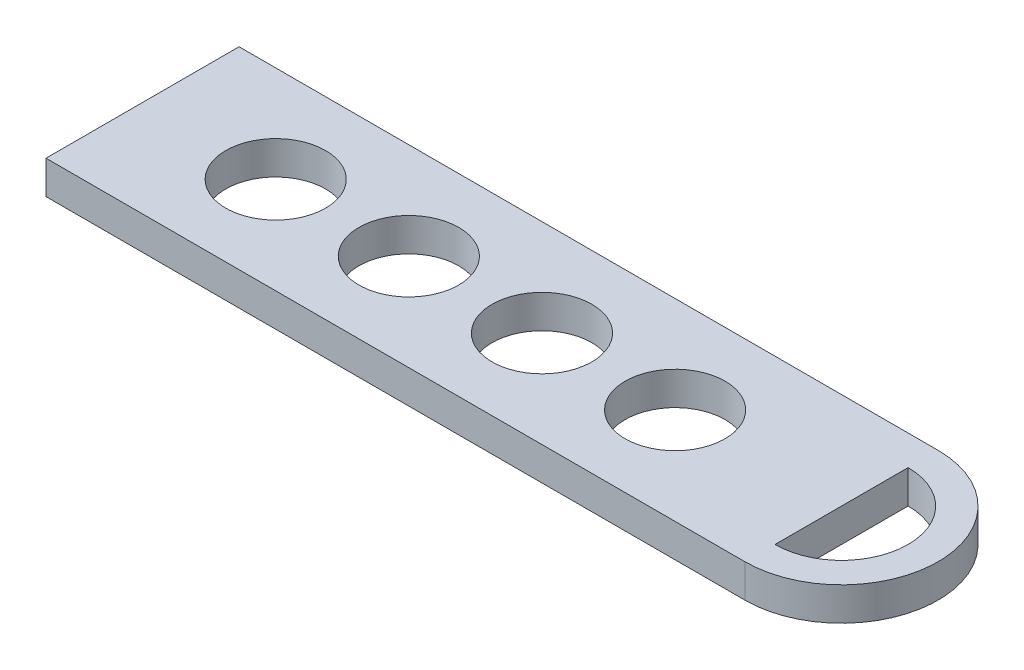
SolidWorks part; units mm, degrees
material "Perspex (TM) GS Acrylic Cast Sheet"
ref_plane "Front Plane" through (0, 0, 0) normal (0, 0, 1) x (1, 0, 0)
ref_plane "Top Plane" through (0, 0, 0) normal (0, 1, 0) x (1, 0, 0)
ref_plane "Right Plane" through (0, 0, 0) normal (1, 0, 0) x (0, 0, -1)
sketch "Sketch1" plane through (0, 0, 0) normal (1, 0, 0) x (0, 0, -1)
  line L1 (-14.5, -2.5) -> (14.5, -2.5)
  line L2 (-14.5, -2.5) -> (-14.5, 2.5)
  line L3 (-14.5, 2.5) -> (14.5, 2.5)
  line L4 (14.5, -2.5) -> (14.5, 2.5)
  line L5 (-14.5, -2.5) -> (14.5, 2.5) construction
  line L6 (-14.5, 2.5) -> (14.5, -2.5) construction
  point P0 (0, 0)
  dimension "D1" = 29
  dimension "D2" = 5
extrude "Boss-Extrude1" add sketch "Sketch1" along normal blind 105
sketch "Sketch2" plane through (0, -2.5, 0) normal (0, -1, 0) x (1, 0, 0)
  line L0 (0, 14.5) -> (0, -14.5) construction
  circle A0 centre (20, 0) radius 7.5
  circle A1 centre (40, 0) radius 7.5
  circle A2 centre (60, 0) radius 7.5
  circle A3 centre (80, 0) radius 7.5
  dimension "D1" = 15
  dimension "D2" = 15
  dimension "D3" = 15
  dimension "D4" = 15
  dimension "D5" = 20
  dimension "D6" = 20
  dimension "D7" = 20
  dimension "D8" = 20
extrude "Cut-Extrude1" cut sketch "Sketch2" against normal blind 105
sketch "Sketch3" plane through (0, -2.5, 0) normal (0, -1, 0) x (1, 0, 0)
  line L0 (105, 14.5) -> (105, -14.5) construction
  line L1 (105, 14.5) -> (105, 10)
  line L2 (105, -10) -> (105, -14.5)
  arc A0 (105, -14.5) -> (105, 14.5) centre (105, 0) ccw
  arc A1 (105, 10) -> (105, -10) centre (105, 0) cw
  dimension "D1" = 14.5
  dimension "D2" = 10
extrude "Boss-Extrude2" add sketch "Sketch3" against normal blind 5
